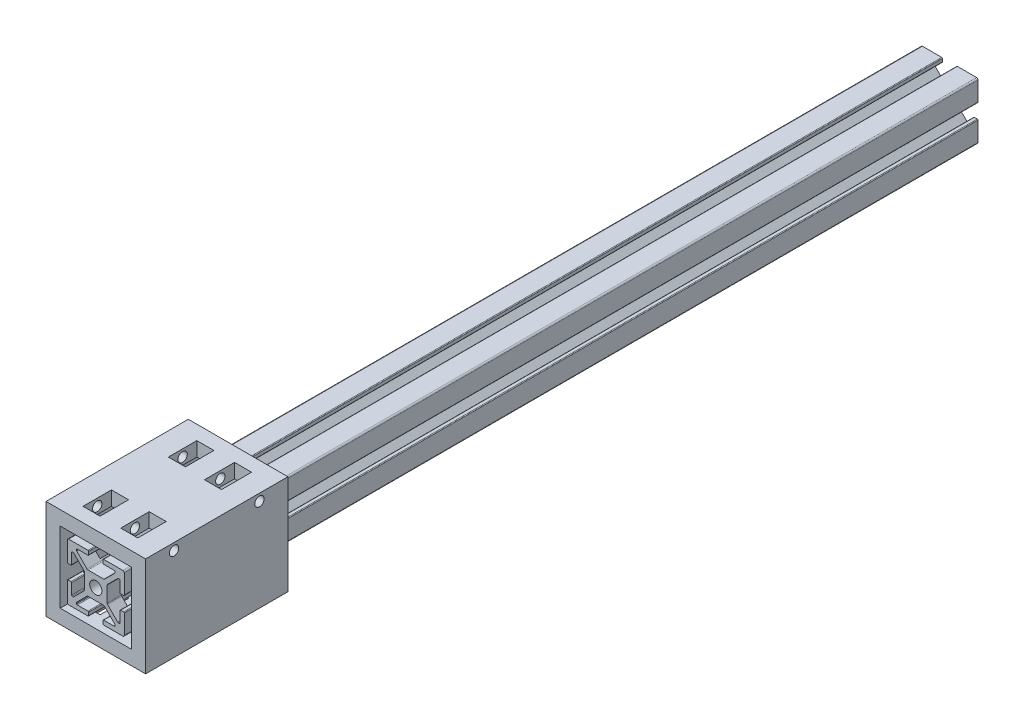
SolidWorks part; units mm, degrees
ref_plane "Спереди" through (0, 0, 0) normal (0, 0, 1) x (1, 0, 0)
ref_plane "Сверху" through (0, 0, 0) normal (0, 1, 0) x (1, 0, 0)
ref_plane "Справа" through (0, 0, 0) normal (1, 0, 0) x (0, 0, -1)
sketch "Эскиз1" plane through (0, 0, 0) normal (0, 0, 1) x (1, 0, 0)
  line L0 (-10, -2.75) -> (-10, -9.5)
  line L1 (-9.5, -10) -> (-2.75, -10)
  line L2 (-2.5, -9.75) -> (-2.5, -8.75)
  line L3 (-2.75, -8.5) -> (-6.5, -8.5)
  line L4 (-6.75, -8.25) -> (-6.75, -7.9142)
  line L5 (-6.6768, -7.7374) -> (-3.0858, -4.1464)
  line L6 (-2.7322, -4) -> (2.7322, -4)
  line L7 (3.0858, -4.1464) -> (6.6768, -7.7374)
  line L8 (6.75, -7.9142) -> (6.75, -8.25)
  line L9 (6.5, -8.5) -> (2.75, -8.5)
  line L10 (2.5, -8.75) -> (2.5, -9.75)
  line L11 (2.75, -10) -> (9.5, -10)
  line L12 (10, -9.5) -> (10, -2.75)
  line L13 (9.75, -2.5) -> (8.75, -2.5)
  line L14 (8.5, -2.75) -> (8.5, -6.5)
  line L15 (8.25, -6.75) -> (7.9142, -6.75)
  line L16 (7.7374, -6.6768) -> (4.1464, -3.0858)
  line L17 (4, -2.7322) -> (4, 2.7322)
  line L18 (4.1464, 3.0858) -> (7.7374, 6.6768)
  line L19 (7.9142, 6.75) -> (8.25, 6.75)
  line L20 (8.5, 6.5) -> (8.5, 2.75)
  line L21 (8.75, 2.5) -> (9.75, 2.5)
  line L22 (10, 2.75) -> (10, 9.5)
  line L23 (9.5, 10) -> (2.75, 10)
  line L24 (2.5, 9.75) -> (2.5, 8.75)
  line L25 (2.75, 8.5) -> (6.5, 8.5)
  line L26 (6.75, 8.25) -> (6.75, 7.8107)
  line L27 (6.75, 7.8107) -> (3.0126, 4.0732)
  line L28 (2.8358, 4) -> (-2.7322, 4)
  line L29 (-3.0858, 4.1464) -> (-6.6768, 7.7374)
  line L30 (-6.75, 7.9142) -> (-6.75, 8.25)
  line L31 (-6.5, 8.5) -> (-2.75, 8.5)
  line L32 (-2.5, 8.75) -> (-2.5, 9.75)
  line L33 (-2.75, 10) -> (-9.5, 10)
  line L34 (-10, 9.5) -> (-10, 2.75)
  line L35 (-9.75, 2.5) -> (-8.75, 2.5)
  line L36 (-8.5, 2.75) -> (-8.5, 6.5)
  line L37 (-8.25, 6.75) -> (-7.9142, 6.75)
  line L38 (-7.7374, 6.6768) -> (-4.1464, 3.0858)
  line L39 (-4, 2.7322) -> (-4, -2.7322)
  line L40 (-4.1464, -3.0858) -> (-7.7374, -6.6768)
  line L41 (-7.9142, -6.75) -> (-8.25, -6.75)
  line L42 (-8.5, -6.5) -> (-8.5, -2.75)
  line L43 (-8.75, -2.5) -> (-9.75, -2.5)
  circle A0 centre (0, 0) radius 2.15
  arc A1 (-10, -9.5) -> (-9.5, -10) centre (-9.5, -9.5) ccw
  arc A2 (-2.75, -10) -> (-2.5, -9.75) centre (-2.75, -9.75) ccw
  arc A3 (-2.5, -8.75) -> (-2.75, -8.5) centre (-2.75, -8.75) ccw
  arc A4 (-6.5, -8.5) -> (-6.75, -8.25) centre (-6.5, -8.25) cw
  arc A5 (-6.75, -7.9142) -> (-6.6768, -7.7374) centre (-6.5, -7.9142) cw
  arc A6 (-3.0858, -4.1464) -> (-2.7322, -4) centre (-2.7322, -4.5) cw
  arc A7 (2.7322, -4) -> (3.0858, -4.1464) centre (2.7322, -4.5) cw
  arc A8 (6.6768, -7.7374) -> (6.75, -7.9142) centre (6.5, -7.9142) cw
  arc A9 (6.75, -8.25) -> (6.5, -8.5) centre (6.5, -8.25) cw
  arc A10 (2.75, -8.5) -> (2.5, -8.75) centre (2.75, -8.75) ccw
  arc A11 (2.5, -9.75) -> (2.75, -10) centre (2.75, -9.75) ccw
  arc A12 (9.5, -10) -> (10, -9.5) centre (9.5, -9.5) ccw
  arc A13 (10, -2.75) -> (9.75, -2.5) centre (9.75, -2.75) ccw
  arc A14 (8.75, -2.5) -> (8.5, -2.75) centre (8.75, -2.75) ccw
  arc A15 (8.5, -6.5) -> (8.25, -6.75) centre (8.25, -6.5) cw
  arc A16 (7.9142, -6.75) -> (7.7374, -6.6768) centre (7.9142, -6.5) cw
  arc A17 (4.1464, -3.0858) -> (4, -2.7322) centre (4.5, -2.7322) cw
  arc A18 (4, 2.7322) -> (4.1464, 3.0858) centre (4.5, 2.7322) cw
  arc A19 (7.7374, 6.6768) -> (7.9142, 6.75) centre (7.9142, 6.5) cw
  arc A20 (8.25, 6.75) -> (8.5, 6.5) centre (8.25, 6.5) cw
  arc A21 (8.5, 2.75) -> (8.75, 2.5) centre (8.75, 2.75) ccw
  arc A22 (9.75, 2.5) -> (10, 2.75) centre (9.75, 2.75) ccw
  arc A23 (10, 9.5) -> (9.5, 10) centre (9.5, 9.5) ccw
  arc A24 (2.75, 10) -> (2.5, 9.75) centre (2.75, 9.75) ccw
  arc A25 (2.5, 8.75) -> (2.75, 8.5) centre (2.75, 8.75) ccw
  arc A26 (6.5, 8.5) -> (6.75, 8.25) centre (6.5, 8.25) cw
  arc A27 (3.0126, 4.0732) -> (2.8358, 4) centre (2.8358, 4.25) cw
  arc A28 (-2.7322, 4) -> (-3.0858, 4.1464) centre (-2.7322, 4.5) cw
  arc A29 (-6.6768, 7.7374) -> (-6.75, 7.9142) centre (-6.5, 7.9142) cw
  arc A30 (-6.75, 8.25) -> (-6.5, 8.5) centre (-6.5, 8.25) cw
  arc A31 (-2.75, 8.5) -> (-2.5, 8.75) centre (-2.75, 8.75) ccw
  arc A32 (-2.5, 9.75) -> (-2.75, 10) centre (-2.75, 9.75) ccw
  arc A33 (-9.5, 10) -> (-10, 9.5) centre (-9.5, 9.5) ccw
  arc A34 (-10, 2.75) -> (-9.75, 2.5) centre (-9.75, 2.75) ccw
  arc A35 (-8.75, 2.5) -> (-8.5, 2.75) centre (-8.75, 2.75) ccw
  arc A36 (-8.5, 6.5) -> (-8.25, 6.75) centre (-8.25, 6.5) cw
  arc A37 (-7.9142, 6.75) -> (-7.7374, 6.6768) centre (-7.9142, 6.5) cw
  arc A38 (-4.1464, 3.0858) -> (-4, 2.7322) centre (-4.5, 2.7322) cw
  arc A39 (-4, -2.7322) -> (-4.1464, -3.0858) centre (-4.5, -2.7322) cw
  arc A40 (-7.7374, -6.6768) -> (-7.9142, -6.75) centre (-7.9142, -6.5) cw
  arc A41 (-8.25, -6.75) -> (-8.5, -6.5) centre (-8.25, -6.5) cw
  arc A42 (-8.5, -2.75) -> (-8.75, -2.5) centre (-8.75, -2.75) ccw
  arc A43 (-9.75, -2.5) -> (-10, -2.75) centre (-9.75, -2.75) ccw
extrude "Бобышка-Вытянуть1" add sketch "Эскиз1" against normal blind 300
sketch "Эскиз2" plane through (0, 0, 0) normal (0, 0, 1) x (1, 0, 0)
  line L1 (-12.5, -12.5) -> (12.5, -12.5)
  line L2 (-12.5, -12.5) -> (-12.5, 12.5)
  line L3 (-12.5, 12.5) -> (12.5, 12.5)
  line L4 (12.5, -12.5) -> (12.5, 12.5)
  line L5 (-12.5, -12.5) -> (12.5, 12.5) construction
  line L6 (-12.5, 12.5) -> (12.5, -12.5) construction
  line L7 (-17.5, 17.5) -> (17.5, 17.5)
  line L8 (-17.5, 17.5) -> (-17.5, -17.5)
  line L9 (-17.5, -17.5) -> (17.5, -17.5)
  line L10 (17.5, 17.5) -> (17.5, -17.5)
  line L11 (-17.5, 17.5) -> (17.5, -17.5) construction
  line L12 (-17.5, -17.5) -> (17.5, 17.5) construction
  point P0 (0, 0)
  point P5 (0, 0)
  dimension "D1" = 25
  dimension "D2" = 35
extrude "Бобышка-Вытянуть2" add sketch "Эскиз2" against normal blind 50 separate body
sketch "Эскиз3" plane through (0, -17.5, 0) normal (0, -1, 0) x (1, 0, 0)
  line L0 (-22.0583, -10) -> (-22.0583, -20) construction
  line L1 (6.75, -44.252) -> (-6.5, -44.252) construction
  line L2 (-16, -44.252) -> (-6.5, -44.252) construction
  line L3 (-22.0583, -20) -> (-22.0583, -30) construction
  line L4 (-22.0583, -30) -> (-22.0583, -40) construction
  line L5 (-22.0583, -40) -> (-22.0583, -50) construction
  line L7 (-9.5, -5) -> (-3.5, -5)
  line L8 (-22.0583, -10) -> (-22.0583, 0) construction
  line L9 (-9.5, -5) -> (-9.5, -15)
  line L10 (-9.5, -15) -> (-3.5, -15)
  line L11 (-3.5, -5) -> (-3.5, -15)
  line L12 (-9.5, -5) -> (-3.5, -15) construction
  line L13 (-9.5, -15) -> (-3.5, -5) construction
  line L14 (3.75, -5) -> (9.75, -5)
  line L15 (3.75, -5) -> (3.75, -15)
  line L16 (3.75, -15) -> (9.75, -15)
  line L17 (9.75, -5) -> (9.75, -15)
  line L18 (3.75, -5) -> (9.75, -15) construction
  line L19 (3.75, -15) -> (9.75, -5) construction
  line L20 (-9.5, -45) -> (-3.5, -45)
  line L21 (-9.5, -45) -> (-9.5, -35)
  line L22 (-9.5, -35) -> (-3.5, -35)
  line L23 (-3.5, -45) -> (-3.5, -35)
  line L24 (-9.5, -45) -> (-3.5, -35) construction
  line L25 (-9.5, -35) -> (-3.5, -45) construction
  line L26 (3.75, -45) -> (9.75, -45)
  line L27 (3.75, -45) -> (3.75, -34.4324)
  line L28 (3.75, -34.4324) -> (9.75, -34.4324)
  line L29 (9.75, -45) -> (9.75, -34.4324)
  line L30 (3.75, -45) -> (9.75, -34.4324) construction
  line L31 (3.75, -34.4324) -> (9.75, -45) construction
  point P7 (-6.5, -10)
  point P16 (6.75, -10)
  point P21 (-6.5, -40)
  point P26 (6.75, -39.7162)
  dimension "D1" = 10
  dimension "D2" = 10
  dimension "D3" = 10
  dimension "D4" = 10
  dimension "D5" = 10
  dimension "D6" = 10
  dimension "D7" = 6
  dimension "D8" = 10
  dimension "D9" = 6
  dimension "D10" = 10
  dimension "D11" = 6
  dimension "D12" = 6
extrude "Вырез-Вытянуть1" cut sketch "Эскиз3" against normal through all
sketch "Эскиз4" plane through (-3.5, 0, 0) normal (-1, 0, 0) x (0, 0, 1)
  circle A0 centre (-10, 15) radius 1.65
  circle A1 centre (-40, 15) radius 1.65
  dimension "D1" = 3.3
  dimension "D2" = 3.3
extrude "Вырез-Вытянуть2" cut sketch "Эскиз4" against normal through all and the other way through all
